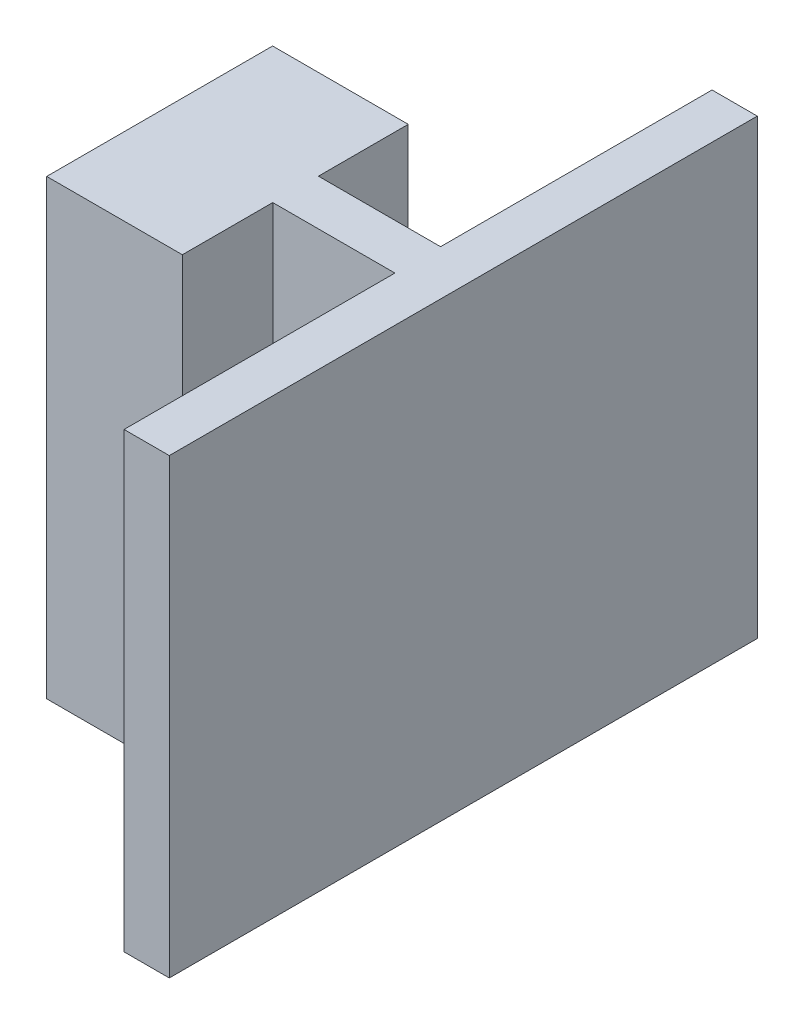
SolidWorks part; units mm, degrees
ref_plane "Front Plane" through (0, 0, 0) normal (0, 0, 1) x (1, 0, 0)
ref_plane "Top Plane" through (0, 0, 0) normal (0, 1, 0) x (1, 0, 0)
ref_plane "Right Plane" through (0, 0, 0) normal (1, 0, 0) x (0, 0, -1)
sketch "Sketch1" plane through (0, 0, 0) normal (0, 1, 0) x (1, 0, 0)
  line L0 (34.29, -12.8155) -> (0, -12.8155)
  line L1 (0, -12.8155) -> (0, -38.1951)
  line L2 (0, -38.1951) -> (-38.0746, -38.1951)
  line L3 (-38.0746, -38.1951) -> (-38.0746, 25.2134)
  line L4 (-38.0746, 25.2134) -> (0, 25.2134)
  line L5 (0, 25.2134) -> (0, 0)
  line L6 (0, 0) -> (34.29, 0)
  line L7 (34.29, 0) -> (34.29, 76.2)
  line L8 (34.29, 76.2) -> (46.99, 76.2)
  line L9 (46.99, 76.2) -> (46.99, -88.8492)
  line L10 (46.99, -88.8492) -> (34.29, -88.8492)
  line L11 (34.29, -88.8492) -> (34.29, -12.8155)
extrude "Boss-Extrude1" add sketch "Sketch1" along normal blind 127
